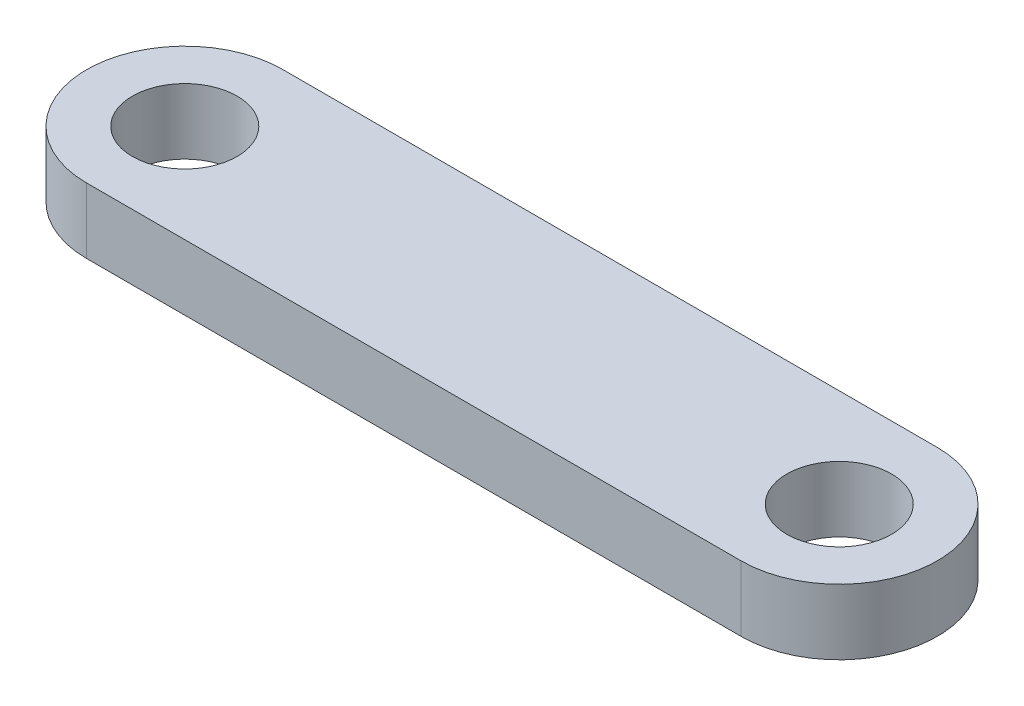
SolidWorks part; units mm, degrees
ref_plane "前视基准面" through (0, 0, 0) normal (0, 0, 1) x (1, 0, 0)
ref_plane "上视基准面" through (0, 0, 0) normal (0, 1, 0) x (1, 0, 0)
ref_plane "右视基准面" through (0, 0, 0) normal (1, 0, 0) x (0, 0, -1)
sketch "草图1" plane through (0, 0, 0) normal (0, 1, 0) x (1, 0, 0)
  line L0 (-25, 0) -> (25, 0) construction
  line L1 (-25, 7.5) -> (25, 7.5)
  line L2 (-25, -7.5) -> (25, -7.5)
  arc A0 (-25, 7.5) -> (-25, -7.5) centre (-25, 0) ccw
  arc A1 (25, -7.5) -> (25, 7.5) centre (25, 0) ccw
  circle A2 centre (-25, 0) radius 4
  circle A3 centre (25, 0) radius 4
  point P2 (0, 0)
  dimension "D1" = 7.5
  dimension "D3" = 8
  dimension "D4" = 8
  dimension "D2" = 50
extrude "凸台-拉伸1" add sketch "草图1" along normal blind 5
